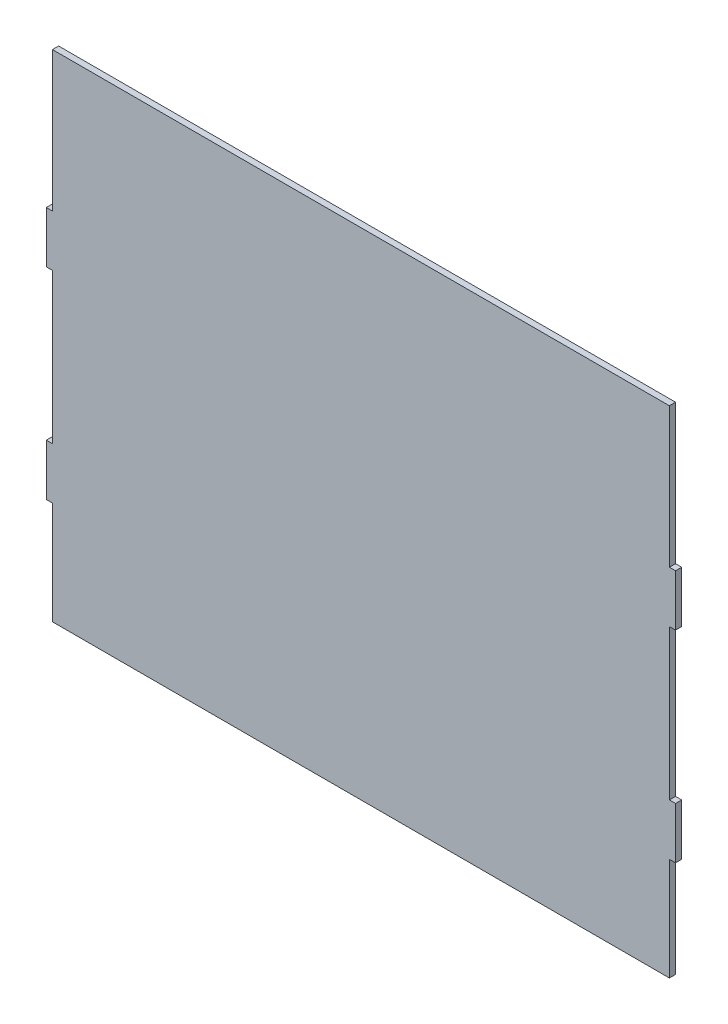
SolidWorks part; units mm, degrees
material "Maple"
ref_plane "Front Plane" through (0, 0, 0) normal (0, 0, 1) x (1, 0, 0)
ref_plane "Top Plane" through (0, 0, 0) normal (0, 1, 0) x (1, 0, 0)
ref_plane "Right Plane" through (0, 0, 0) normal (1, 0, 0) x (0, 0, -1)
sketch "Sketch1" plane through (0, 0, 0) normal (0, 0, 1) x (1, 0, 0)
  line L1 (-300, 241) -> (300, 241)
  line L2 (-300, 241) -> (-300, 105)
  line L3 (-300, -241) -> (300, -241)
  line L4 (300, 241) -> (300, 105)
  line L5 (-300, 241) -> (300, -241) construction
  line L6 (-300, -241) -> (300, 241) construction
  line L7 (-306, 105) -> (-300, 105)
  line L8 (-306, 105) -> (-306, 55)
  line L9 (-306, 55) -> (-300, 55)
  line L11 (-300, 189) -> (-282.5, 164) construction
  line L12 (-300, -141) -> (-300, -241)
  line L13 (0, 241) -> (0, -241) construction
  line L14 (306, 55) -> (300, 55)
  line L15 (306, 105) -> (306, 55)
  line L16 (306, 105) -> (300, 105)
  line L20 (-306, -91) -> (-300, -91)
  line L23 (-306, -141) -> (-306, -91)
  line L24 (-300, 55) -> (-300, -91)
  line L26 (300, 55) -> (300, -91)
  line L27 (306, -141) -> (306, -91)
  line L28 (306, -91) -> (300, -91)
  line L31 (-306, -141) -> (-300, -141)
  line L33 (300, -241) -> (300, -141)
  line L34 (300, -141) -> (306, -141)
  point P0 (0, 0)
  point P6 (-300, 189)
  point P31 (-156.1598, -207)
  dimension "D1" = 600
  dimension "D2" = 482
  dimension "D3" = 136
  dimension "D4" = 100
  dimension "D5" = 50
  dimension "D6" = 6
  dimension "D7" = 100
  dimension "D8" = 6
extrude "Boss-Extrude1" add sketch "Sketch1" along normal blind 6
